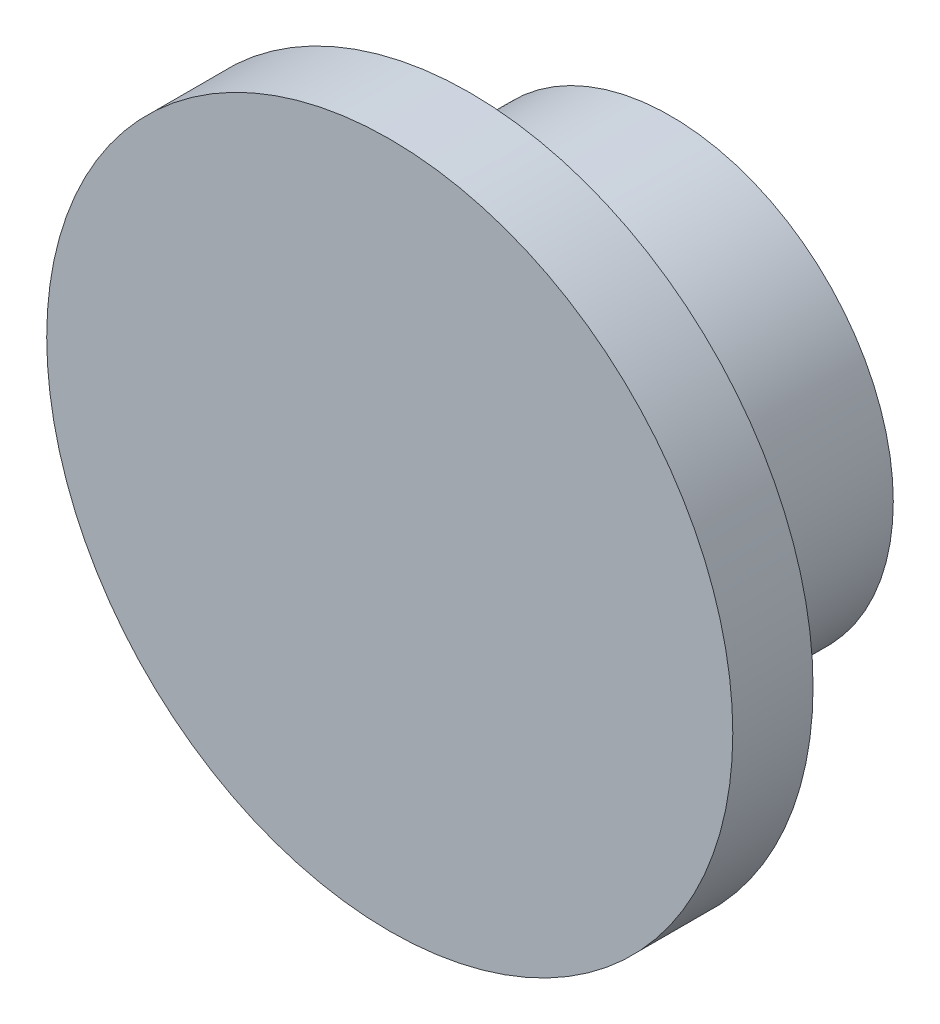
SolidWorks part; units mm, degrees
ref_plane "Front Plane" through (0, 0, 0) normal (0, 0, 1) x (1, 0, 0)
ref_plane "Top Plane" through (0, 0, 0) normal (0, 1, 0) x (1, 0, 0)
ref_plane "Right Plane" through (0, 0, 0) normal (1, 0, 0) x (0, 0, -1)
sketch "Sketch1" plane through (0, 0, 0) normal (0, 0, 1) x (1, 0, 0)
  circle A0 centre (0, 0) radius 2.55
  circle A3 centre (0, 0) radius 2.35 construction
  circle A4 centre (0, 0) radius 5.55
  point P3 (0, 0)
  dimension "D1" = 4.7
  dimension "D2" = 0.2
  dimension "D3" = 3
extrude "Boss-Extrude1" add sketch "Sketch1" against normal blind 5
sketch "Sketch2" plane through (0, 0, 0) normal (0, 0, 1) x (1, 0, 0)
  circle A2 centre (0, 0) radius 8.55
  circle A3 centre (0, 0) radius 8.55
  dimension "D1" = 3
extrude "Boss-Extrude2" add sketch "Sketch2" along normal blind 2
